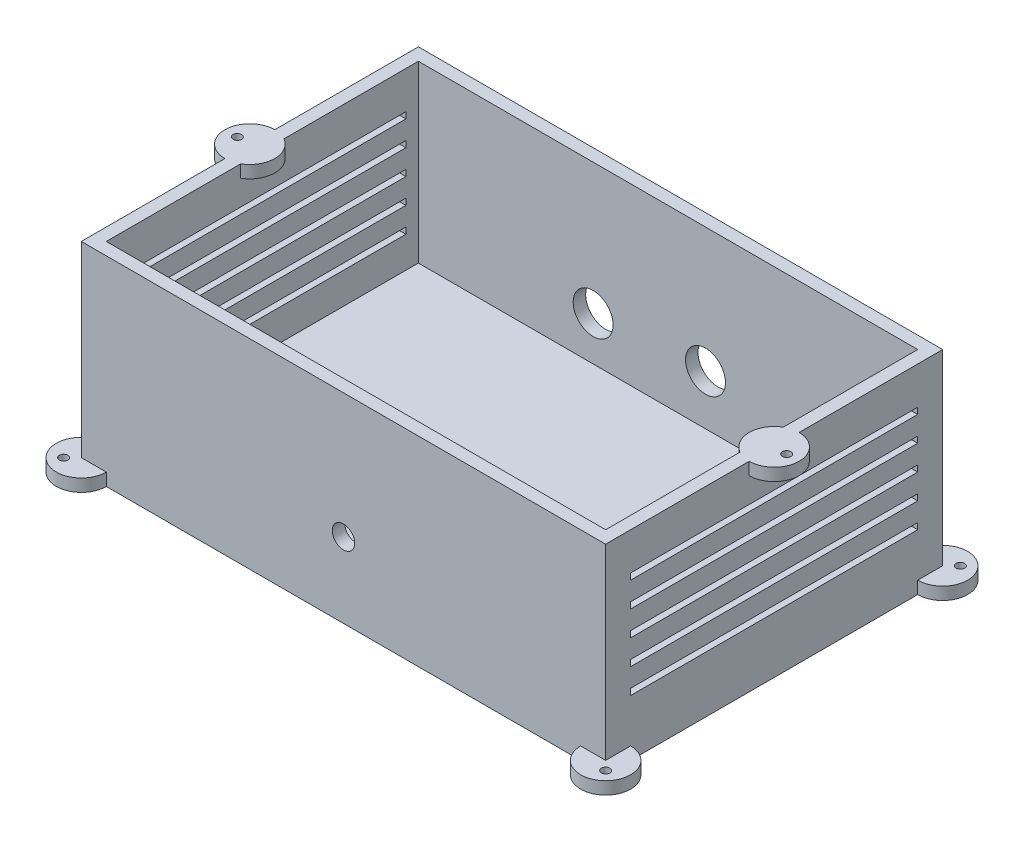
SolidWorks part; units mm, degrees
ref_plane "Front Plane" through (0, 0, 0) normal (0, 0, 1) x (1, 0, 0)
ref_plane "Top Plane" through (0, 0, 0) normal (0, 1, 0) x (1, 0, 0)
ref_plane "Right Plane" through (0, 0, 0) normal (1, 0, 0) x (0, 0, -1)
sketch "Sketch1" plane through (0, 0, 0) normal (0, 1, 0) x (1, 0, 0)
  line L0 (0, 0) -> (210, 0)
  line L1 (210, 0) -> (210, -135)
  line L2 (210, -135) -> (0, -135)
  line L3 (0, -135) -> (0, 0)
  line L4 (0, -135) -> (5, -135)
  line L5 (5, -135) -> (5, -5)
  line L6 (5, -5) -> (205, -5)
  line L7 (205, -5) -> (205, -130)
  line L8 (205, -130) -> (5, -130)
extrude "Boss-Extrude1" add sketch "Sketch1" along normal blind 70
sketch "Sketch2" plane through (0, 0, 0) normal (0, -1, 0) x (-1, 0, 0)
  line L0 (0, -135) -> (-210, -135)
  line L1 (-210, -135) -> (-210, 0)
  line L2 (-210, 0) -> (0, 0)
  line L3 (0, 0) -> (0, -135)
extrude "Boss-Extrude2" add sketch "Sketch2" along normal blind 10
sketch "Sketch3" plane through (0, -10, 0) normal (0, -1, 0) x (-1, 0, 0)
  circle A0 centre (-210, 0) radius 10
  circle A1 centre (0, 0) radius 10
  circle A2 centre (0, -135) radius 10
  circle A3 centre (-210, -135) radius 10
extrude "Boss-Extrude5" add sketch "Sketch3" against normal blind 5
sketch "Sketch7" plane through (0, -5, 0) normal (0, 1, 0) x (1, 0, 0)
  line L0 (0, 0) -> (-7.0711, 7.0711)
  line L1 (210, -135) -> (217.0711, -142.0711)
  line L2 (210, 0) -> (217.0711, 7.0711)
  line L3 (0, -135) -> (-7.0711, -142.0711)
  arc A0 (10, 0) -> (0, -10) centre (0, 0) ccw construction
  arc A1 (200, -135) -> (210, -125) centre (210, -135) ccw construction
  arc A2 (210, -10) -> (200, 0) centre (210, 0) ccw construction
  arc A3 (0, -125) -> (10, -135) centre (0, -135) ccw construction
  circle A4 centre (-3.5355, 3.5355) radius 1.7
  circle A5 centre (213.5355, 3.5355) radius 1.7
  circle A6 centre (213.5355, -138.5355) radius 1.7
  circle A7 centre (-3.5355, -138.5355) radius 1.7
extrude "Cut-Extrude2" cut sketch "Sketch7" against normal blind 5 contours L1 A6 | L1 A6 | L2 A5 | L2 A5 | L0 A4 | L0 A4 | L3 A7 | L3 A7
sketch "Sketch9" plane through (0, 0, 0) normal (0, 1, 0) x (1, 0, 0)
  line L0 (200, -135) -> (200, -125)
  line L1 (200, -125) -> (210, -125)
  line L2 (210, -125) -> (210, -10)
  line L3 (210, -10) -> (200, -10)
  line L4 (200, -10) -> (205, -15)
  line L5 (205, -5) -> (205, -130) construction
  line L6 (205, -15) -> (195, -5)
  line L7 (5, -5) -> (205, -5) construction
  line L8 (195, -5) -> (195, -130)
  line L9 (205, -130) -> (5, -130) construction
  line L10 (195, -130) -> (205, -120)
  line L11 (205, -120) -> (205, -15)
  line M2 (205, -130) -> (205, -5)
extrude "Cut-Extrude3" cut sketch "Sketch9" against normal blind 10 contours L8 L10 L4 L6 M2
sketch "Sketch10" plane through (0, 0, 0) normal (0, 1, 0) x (1, 0, 0)
  line L0 (195, -5) -> (195, -130)
  line L1 (195, -130) -> (185, -130)
  line L2 (195, -130) -> (5, -130) construction
  line L3 (185, -130) -> (185, -5)
  line L4 (5, -5) -> (205, -5) construction
  line L5 (185, -5) -> (195, -5)
extrude "Cut-Extrude4" cut sketch "Sketch10" against normal blind 10
sketch "Sketch11" plane through (0, 70, 0) normal (0, 1, 0) x (1, 0, 0)
  line L0 (210, 0) -> (210, -135) construction
  line L1 (210, -67.5) -> (220, -67.5)
  line L2 (0, -135) -> (0, 0) construction
  line L3 (0, -67.5) -> (-10, -67.5)
  circle A0 centre (210, -67.5) radius 10
  circle A1 centre (0, -67.5) radius 10
  circle A2 centre (-5, -67.5) radius 1.7
  circle A3 centre (215, -67.5) radius 1.7
  line M2 (5, -130) -> (5, -5)
  line M4 (205, -5) -> (205, -130)
  line M5 (0, 0) -> (0, -135)
  line M7 (210, -135) -> (210, 0)
extrude "Boss-Extrude6" add sketch "Sketch11" against normal blind 5 contours A3 L1 A0 M7 | A0 M4 | A0 M7 M4 | A3 L1 A0 M7 | A1 M2 | A1 M5 M2 | A2 L3 A1 M5 | A2 L3 A1 M5
sketch "Sketch12" plane through (0, 0, 0) normal (0, 0, -1) x (-1, 0, 0)
  line L0 (0, -10) -> (-75, -10)
  line L1 (-10, -10) -> (-200, -10) construction
  line L2 (-75, -10) -> (-75, 17.5)
  line L3 (0, -10) -> (-120, -10)
  line L4 (-120, -10) -> (-120, 20)
  circle A1 centre (-75, 17.5) radius 8
  circle A2 centre (-120, 20) radius 8
extrude "Cut-Extrude5" cut sketch "Sketch12" against normal blind 10
sketch "Sketch15" plane through (0, 0, 135) normal (0, 0, 1) x (1, 0, 0)
  line L0 (105, -10) -> (105, 0)
  line L1 (200, -10) -> (10, -10) construction
  line L2 (105, 0) -> (105, 20)
  circle A0 centre (105, 20) radius 4.5
extrude "Cut-Extrude6" cut sketch "Sketch15" against normal blind 10
sketch "Sketch18" plane through (210, 0, 0) normal (1, 0, 0) x (0, 0, -1)
  line L2 (-125, 45) -> (-125, 42.5)
  line L3 (-125, 52.5) -> (-10, 52.5)
  line L4 (-125, 32.5) -> (-10, 32.5)
  line L5 (-10, 25) -> (-10, 22.5)
  line L6 (-10, 12.5) -> (-125, 12.5)
  line L7 (-125, 12.5) -> (-125, 15)
  line L8 (-125, 15) -> (-10, 15)
  line L9 (-10, 22.5) -> (-125, 22.5)
  line L10 (-125, 22.5) -> (-125, 25)
  line L11 (-125, 25) -> (-10, 25)
  line L12 (-125, 32.5) -> (-125, 35)
  line L13 (-125, 35) -> (-10, 35)
  line L14 (-10, 35) -> (-10, 32.5)
  line L15 (-125, 42.5) -> (-10, 42.5)
  line L16 (-10, 42.5) -> (-10, 45)
  line L17 (-10, 45) -> (-125, 45)
  line L18 (-10, 52.5) -> (-10, 55)
  line L19 (-10, 55) -> (-125, 55)
  line L20 (-125, 55) -> (-125, 52.5)
  line L21 (-10, 15) -> (-10, 12.5)
  point P0 (0, 0)
extrude "Cut-Extrude7" cut sketch "Sketch18" against normal blind 220
